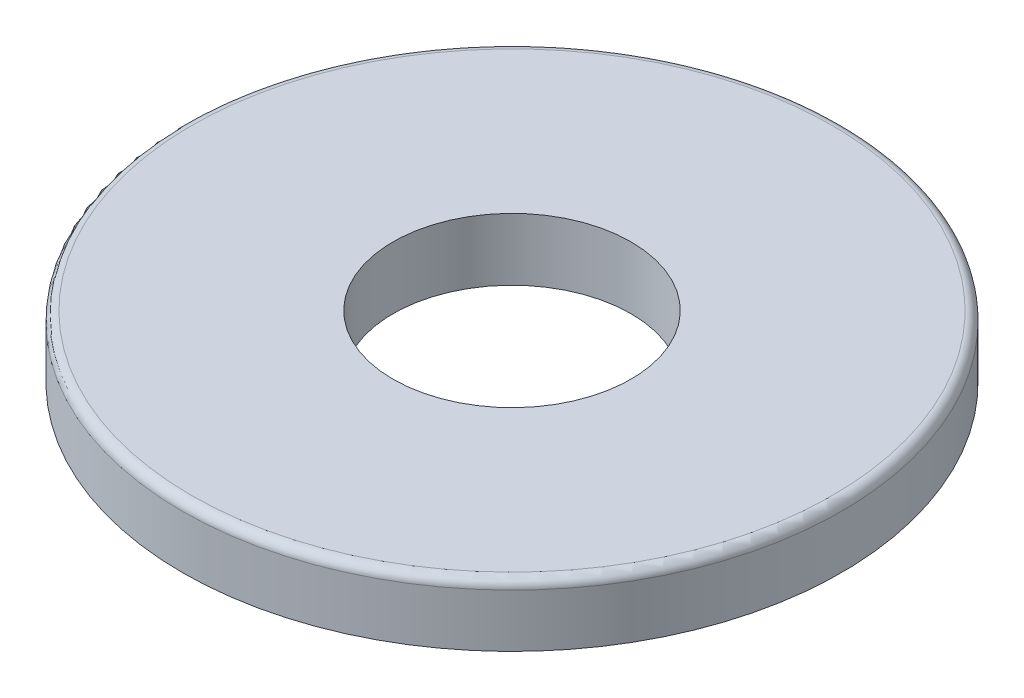
SolidWorks part; units mm, degrees
ref_plane "Спереди" through (0, 0, 0) normal (0, 0, 1) x (1, 0, 0)
ref_plane "Сверху" through (0, 0, 0) normal (0, 1, 0) x (1, 0, 0)
ref_plane "Справа" through (0, 0, 0) normal (1, 0, 0) x (0, 0, -1)
sketch "Эскиз1" plane through (0, 0, 0) normal (0, 1, 0) x (1, 0, 0)
  circle A0 centre (0, 0) radius 3.25
  circle A1 centre (0, 0) radius 9
extrude "Вытянуть1" add sketch "Эскиз1" along normal blind 1.7
fillet "Скругление1" radius 0.25 1 edges at (0, 1.7, 9)
